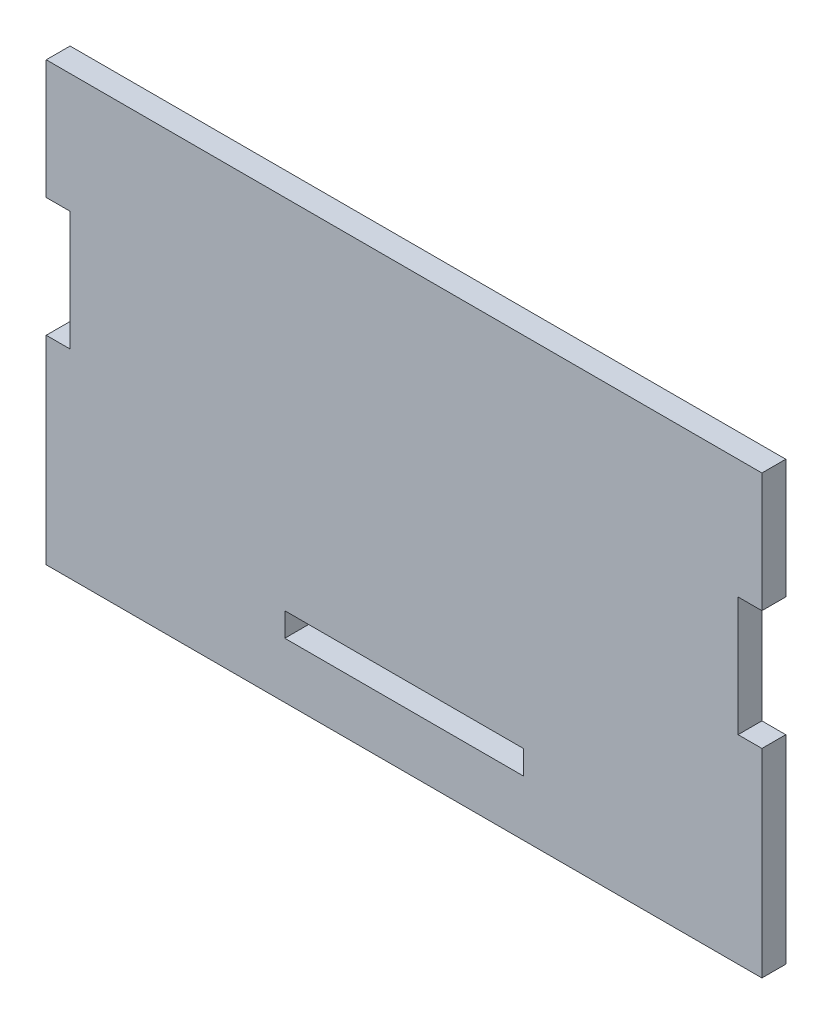
SolidWorks part; units mm, degrees
ref_plane "Front Plane" through (0, 0, 0) normal (0, 0, 1) x (1, 0, 0)
ref_plane "Top Plane" through (0, 0, 0) normal (0, 1, 0) x (1, 0, 0)
ref_plane "Right Plane" through (0, 0, 0) normal (1, 0, 0) x (0, 0, -1)
sketch "Sketch1" plane through (0, 0, 0) normal (0, 0, 1) x (1, 0, 0)
  line L0 (-45, 12.5) -> (-42, 12.5)
  line L1 (-45, -27.5) -> (45, -27.5)
  line L2 (-45, -27.5) -> (-45, 27.5)
  line L3 (-45, 27.5) -> (45, 27.5)
  line L4 (45, -27.5) -> (45, 27.5)
  line L5 (-45, -27.5) -> (45, 27.5) construction
  line L6 (-45, 27.5) -> (45, -27.5) construction
  line L7 (-42, 12.5) -> (-42, -2.5)
  line L8 (-42, -2.5) -> (-45, -2.5)
  line L9 (45, -2.5) -> (42, -2.5)
  line L10 (42, -2.5) -> (42, 12.5)
  line L11 (42, 12.5) -> (45, 12.5)
  line L13 (-15, -20.5) -> (15, -20.5)
  line L14 (-15, -20.5) -> (-15, -17.5)
  line L15 (-15, -17.5) -> (15, -17.5)
  line L16 (15, -20.5) -> (15, -17.5)
  line L17 (-15, -20.5) -> (15, -17.5) construction
  line L18 (-15, -17.5) -> (15, -20.5) construction
  point P0 (0, 0)
  point P12 (0, -19)
  dimension "D1" = 90
  dimension "D2" = 55
  dimension "D3" = 15
  dimension "D4" = 25
  dimension "D5" = 15
  dimension "D6" = 3
  dimension "D7" = 3
  dimension "D8" = 30
  dimension "D9" = 3
  dimension "D10" = 0
  dimension "D11" = 7
extrude "Boss-Extrude1" add sketch "Sketch1" along normal blind 3
